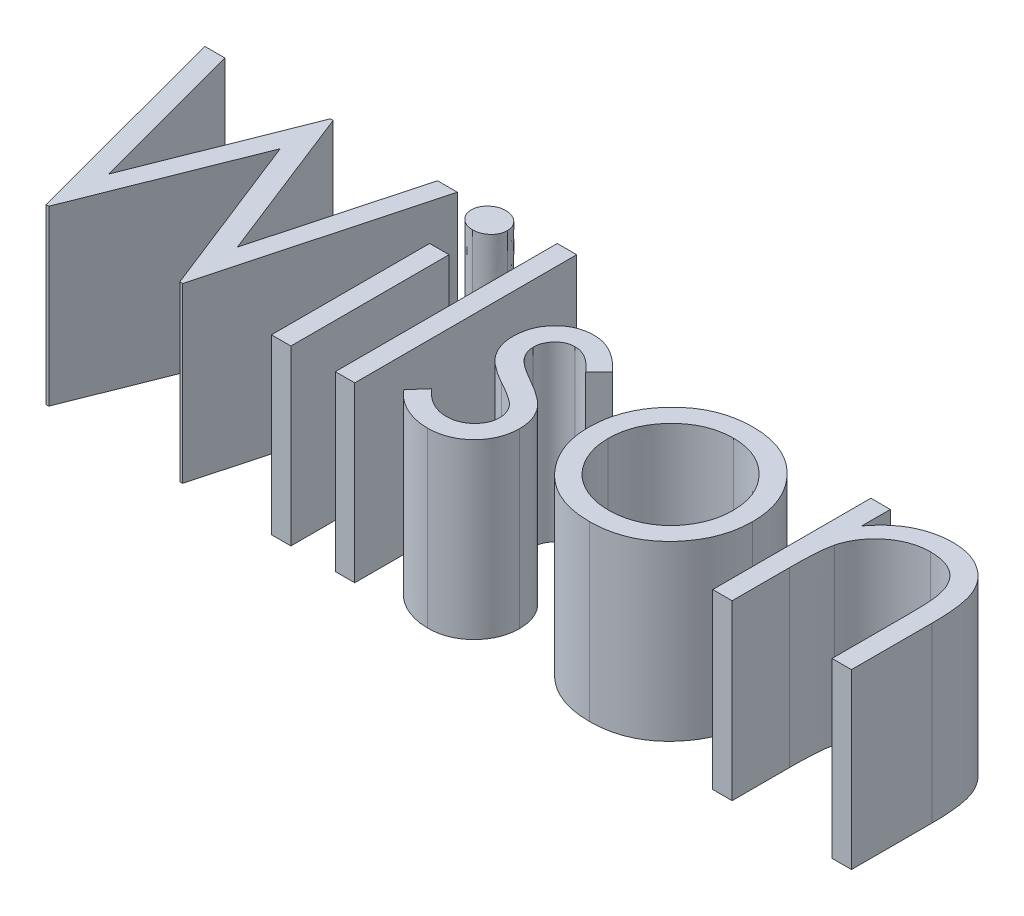
SolidWorks part; units mm, degrees
ref_plane "Front Plane" through (0, 0, 0) normal (0, 0, 1) x (1, 0, 0)
ref_plane "Top Plane" through (0, 0, 0) normal (0, 1, 0) x (1, 0, 0)
ref_plane "Right Plane" through (0, 0, 0) normal (1, 0, 0) x (0, 0, -1)
sketch "Sketch1" plane through (0, 0, 0) normal (0, 1, 0) x (1, 0, 0)
  text T0 "Wilson"
extrude "Boss-Extrude1" add sketch "Sketch1" along normal blind 2.54
